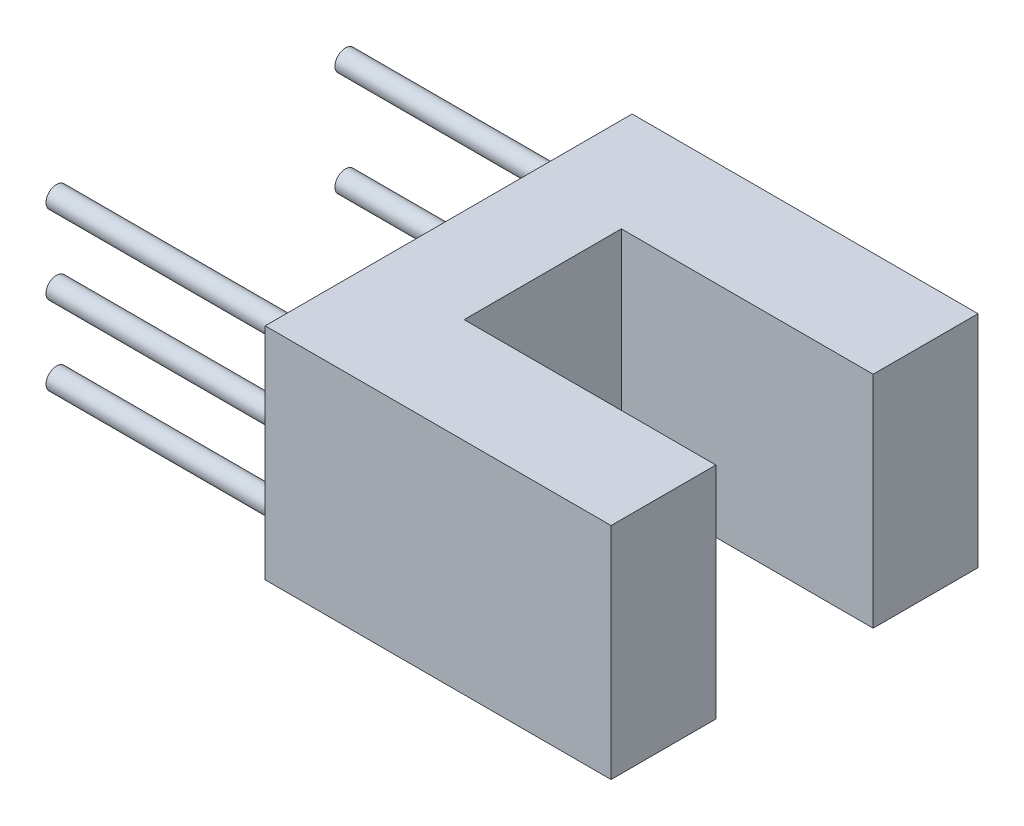
SolidWorks part; units mm, degrees
ref_plane "Front Plane" through (0, 0, 0) normal (0, 0, 1) x (1, 0, 0)
ref_plane "Top Plane" through (0, 0, 0) normal (0, 1, 0) x (1, 0, 0)
ref_plane "Right Plane" through (0, 0, 0) normal (1, 0, 0) x (0, 0, -1)
sketch "Sketch1" plane through (0, 0, 0) normal (1, 0, 0) x (0, 0, -1)
  line L1 (0, 0) -> (8.89, 0)
  line L2 (0, 0) -> (0, 5.33)
  line L3 (0, 5.33) -> (8.89, 5.33)
  line L4 (8.89, 0) -> (8.89, 5.33)
  dimension "D1" = 5.33
  dimension "D2" = 8.89
extrude "Boss-Extrude1" add sketch "Sketch1" along normal blind 8.38
sketch "Sketch2" plane through (8.38, 0, 0) normal (1, 0, 0) x (0, 0, -1)
  line L0 (8.89, 5.33) -> (0, 5.33) construction
  line L1 (2.54, 5.33) -> (6.35, 5.33)
  line L2 (2.54, 5.33) -> (2.54, 0)
  line L3 (2.54, 0) -> (6.35, 0)
  line L4 (6.35, 5.33) -> (6.35, 0)
  line L5 (0, 0) -> (8.89, 0) construction
  line L6 (0, 5.33) -> (0, 0) construction
  dimension "D1" = 2.54
  dimension "D2" = 3.81
extrude "Cut-Extrude1" cut sketch "Sketch2" against normal blind 6.1
sketch "Sketch3" plane through (0, 0, 0) normal (-1, 0, 0) x (0, 0, 1)
  line L0 (-8.89, 2.665) -> (0, 2.665) construction
  line L1 (-8.89, 0) -> (-8.89, 5.33) construction
  line L2 (0, 5.33) -> (0, 0) construction
  line L3 (-4.445, 5.33) -> (-4.445, 0) construction
  line L4 (-8.89, 5.33) -> (0, 5.33) construction
  line L5 (0, 0) -> (-8.89, 0) construction
  line L6 (-0.945, 4.57) -> (-0.945, 0.76) construction
  line L7 (-7.945, 3.935) -> (-7.945, 1.395) construction
  circle A0 centre (-7.945, 3.935) radius 0.255
  circle A1 centre (-7.945, 1.395) radius 0.255
  circle A2 centre (-0.945, 4.57) radius 0.255
  circle A3 centre (-0.945, 2.665) radius 0.255
  circle A4 centre (-0.945, 0.76) radius 0.255
  dimension "D1" = 0.51
  dimension "D2" = 7
  dimension "D3" = 3.5
  dimension "D4" = 2.54
  dimension "D5" = 1.905
extrude "Boss-Extrude2" add sketch "Sketch3" along normal blind 6
